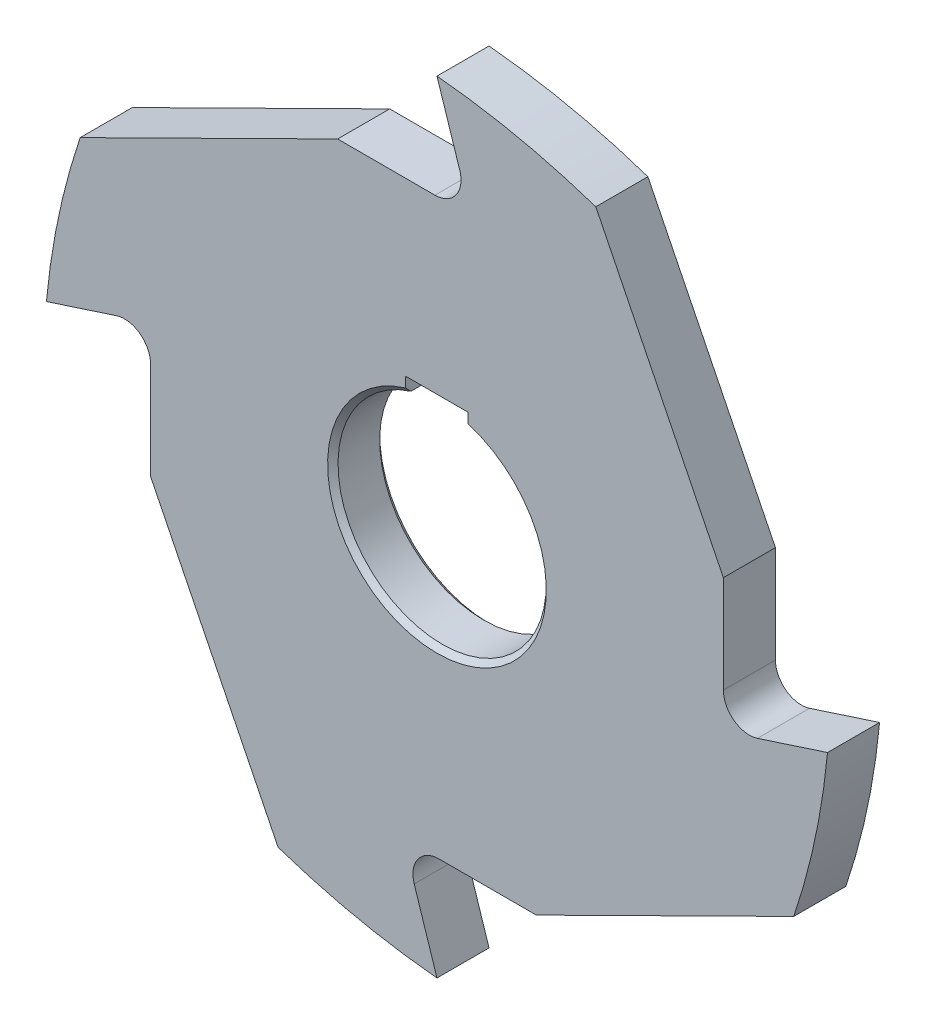
SolidWorks part; units mm, degrees
material "Cast Alloy Steel"
ref_plane "Front Plane" through (0, 0, 0) normal (0, 0, 1) x (1, 0, 0)
ref_plane "Top Plane" through (0, 0, 0) normal (0, 1, 0) x (1, 0, 0)
ref_plane "Right Plane" through (0, 0, 0) normal (1, 0, 0) x (0, 0, -1)
sketch "Sketch1" plane through (0, 0, 0) normal (0, 0, 1) x (1, 0, 0)
  line L0 (-55, 0) -> (55, 0) construction
  line L1 (0, -75) -> (0, 75) construction
  line L2 (-52.0911, 75) -> (52.0911, 75) construction
  line L3 (-52.0911, 55) -> (-50.9902, 55) construction
  line L4 (-6, 22.0788) -> (6, 22.0788)
  line L5 (-6, 19.0788) -> (-6, 22.0788)
  line L6 (0, 75) -> (30.5052, 68.5159) construction
  line L7 (6, 19.0788) -> (6, 22.0788)
  line L8 (0, 55) -> (5, 55) construction
  line L9 (-0.3835, 55) -> (-20, 55)
  line L10 (0, 75) -> (4.3718, 61.5451)
  line L11 (55, -75) -> (55, 75) construction
  line L12 (-55, -75) -> (-55, 75) construction
  line L13 (6, 19.0788) -> (104, 19.0788) construction
  line L14 (55, 0) -> (55, 19.0788)
  line L15 (55, 19.0788) -> (30.5052, 68.5159)
  line L16 (5, -75) -> (5, 75) construction
  line L17 (-20, -75) -> (-20, 75) construction
  line L18 (-20, 55) -> (52.0911, 55) construction
  line L19 (-52.0911, 55) -> (52.0911, 55) construction
  line L20 (55, 0.3835) -> (55, 20)
  line L21 (75, 0) -> (61.5451, -4.3718)
  line L22 (19.0788, -55) -> (68.5159, -30.5052)
  line L23 (0, -55) -> (19.0788, -55)
  line L24 (0.3835, -55) -> (20, -55)
  line L25 (0, -75) -> (-4.3718, -61.5451)
  line L26 (-55, -19.0788) -> (-30.5052, -68.5159)
  line L27 (-55, 0) -> (-55, -19.0788)
  line L28 (-55, -0.3835) -> (-55, -20)
  line L29 (-75, 0) -> (-61.5451, 4.3718)
  line L30 (-19.0788, 55) -> (-68.5159, 30.5052)
  line L31 (0, 55) -> (-19.0788, 55)
  circle A0 centre (0, 0) radius 75
  arc A1 (-6, 19.0788) -> (6, 19.0788) centre (0, 0) ccw
  arc A2 (-0.3835, 55) -> (4.3718, 61.5451) centre (-0.3835, 60) ccw
  arc A3 (0, 75) -> (30.5052, 68.5159) centre (-12.6276, -59.4081) cw
  arc A4 (55, 0.3835) -> (61.5451, -4.3718) centre (60, 0.3835) ccw
  arc A5 (75, 0) -> (68.5159, -30.5052) centre (-59.4081, 12.6276) cw
  arc A6 (0.3835, -55) -> (-4.3718, -61.5451) centre (0.3835, -60) ccw
  arc A7 (0, -75) -> (-30.5052, -68.5159) centre (12.6276, 59.4081) cw
  arc A8 (-55, -0.3835) -> (-61.5451, 4.3718) centre (-60, -0.3835) ccw
  arc A9 (-75, 0) -> (-68.5159, 30.5052) centre (59.4081, -12.6276) cw
  point P4 (0, 0)
  point P7 (0, 0)
  point P18 (0, 75)
  point P67 (0, 0)
  dimension "D1" = 150
  dimension "D2" = 40
  dimension "D7" = 5
  dimension "D12" = 135
  dimension "D13" = 5
  dimension "D3" = 3
  dimension "D4" = 12
  dimension "D5" = 6
  dimension "D6" = 20
  dimension "D8" = 60
  dimension "D9" = 18
  dimension "D10" = 55
  dimension "D11" = 55
  dimension "D14" = 25
  dimension "D15" = 4
extrude "Boss-Extrude1" add sketch "Sketch1" against normal blind 10
chamfer "Chamfer1" distance 1 angle 45 2 edges at (0, -20, -10) (0, -20, 0)
